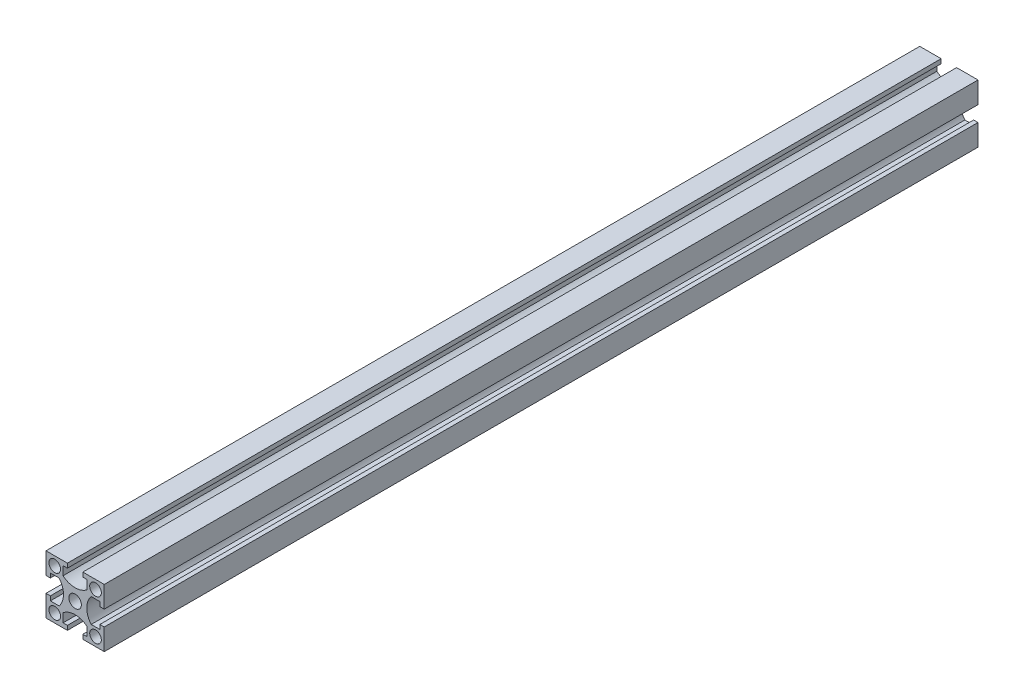
SolidWorks part; units mm, degrees
material "6061-T6 (SS)"
ref_plane "정면" through (0, 0, 0) normal (0, 0, 1) x (1, 0, 0)
ref_plane "윗면" through (0, 0, 0) normal (0, 1, 0) x (1, 0, 0)
ref_plane "우측면" through (0, 0, 0) normal (1, 0, 0) x (0, 0, -1)
sketch "스케치1" plane through (0, 0, 0) normal (0, 0, 1) x (1, 0, 0)
  line L1 (-10, 10) -> (10, 10)
  line L2 (-10, 10) -> (-10, -10)
  line L3 (-10, -10) -> (10, -10)
  line L4 (10, 10) -> (10, -10)
  line L5 (-10, 10) -> (10, -10) construction
  line L6 (-10, -10) -> (10, 10) construction
  point P0 (0, 0)
  dimension "D1" = 20
  dimension "D2" = 20
extrude "보스-돌출1" add sketch "스케치1" along normal blind 300
sketch "스케치2" plane through (0, 0, 300) normal (0, 0, 1) x (1, 0, 0)
  line L0 (-2.65, 10) -> (-2.65, 8.5)
  line L1 (10, 10) -> (-10, 10) construction
  line L2 (-2.65, 8.5) -> (-4.15, 8.5)
  line L3 (-4.15, 8.5) -> (-4.15, 5.5)
  line L4 (-2.65, 10) -> (2.65, 10)
  line L5 (2.65, 10) -> (2.65, 8.5)
  line L6 (2.65, 8.5) -> (4.15, 8.5)
  line L7 (4.15, 8.5) -> (4.15, 5.5)
  line L8 (10, 2.65) -> (8.5, 2.65)
  line L9 (8.5, 2.65) -> (8.5, 4.15)
  line L10 (8.5, 4.15) -> (5.5, 4.15)
  line L11 (10, 2.65) -> (10, -2.65)
  line L12 (10, -2.65) -> (8.5, -2.65)
  line L13 (8.5, -2.65) -> (8.5, -4.15)
  line L14 (8.5, -4.15) -> (5.5, -4.15)
  line L15 (2.65, -10) -> (2.65, -8.5)
  line L16 (2.65, -8.5) -> (4.15, -8.5)
  line L17 (4.15, -8.5) -> (4.15, -5.5)
  line L18 (2.65, -10) -> (-2.65, -10)
  line L19 (-2.65, -10) -> (-2.65, -8.5)
  line L20 (-2.65, -8.5) -> (-4.15, -8.5)
  line L21 (-4.15, -8.5) -> (-4.15, -5.5)
  line L22 (-10, -2.65) -> (-8.5, -2.65)
  line L23 (-8.5, -2.65) -> (-8.5, -4.15)
  line L24 (-8.5, -4.15) -> (-5.5, -4.15)
  line L25 (-10, -2.65) -> (-10, 2.65)
  line L26 (-10, 2.65) -> (-8.5, 2.65)
  line L27 (-8.5, 2.65) -> (-8.5, 4.15)
  line L28 (-8.5, 4.15) -> (-5.5, 4.15)
  arc A1 (-4.15, 5.5) -> (4.15, 5.5) centre (0, 10.4908) ccw
  arc A2 (5.5, 4.15) -> (5.5, -4.15) centre (10.4908, 0) ccw
  arc A3 (4.15, -5.5) -> (-4.15, -5.5) centre (0, -10.4908) ccw
  arc A4 (-5.5, -4.15) -> (-5.5, 4.15) centre (-10.4908, 0) ccw
  circle A5 centre (0, 0) radius 2.15
  circle A6 centre (-7, 7) radius 2
  circle A7 centre (7, 7) radius 2
  circle A8 centre (7, -7) radius 2
  circle A9 centre (-7, -7) radius 2
  point P4 (-2.65, 9.25)
  point P43 (0, 0)
  dimension "D2" = 1.5
  dimension "D8" = 4.3
  dimension "D9" = 4
  dimension "D10" = 4
  dimension "D11" = 4
  dimension "D12" = 4
  dimension "D1" = 5.3
  dimension "D3" = 8.3
  dimension "D4" = 4.15
  dimension "D5" = 2.65
  dimension "D6" = 4
  dimension "D7" = 3
  dimension "D13" = 14
  dimension "D14" = 7
  dimension "D15" = 7
  dimension "D16" = 7
  dimension "D17" = 14
  dimension "D18" = 7
  dimension "D19" = 7
  dimension "D20" = 7
extrude "컷-돌출1" cut sketch "스케치2" against normal blind 300
